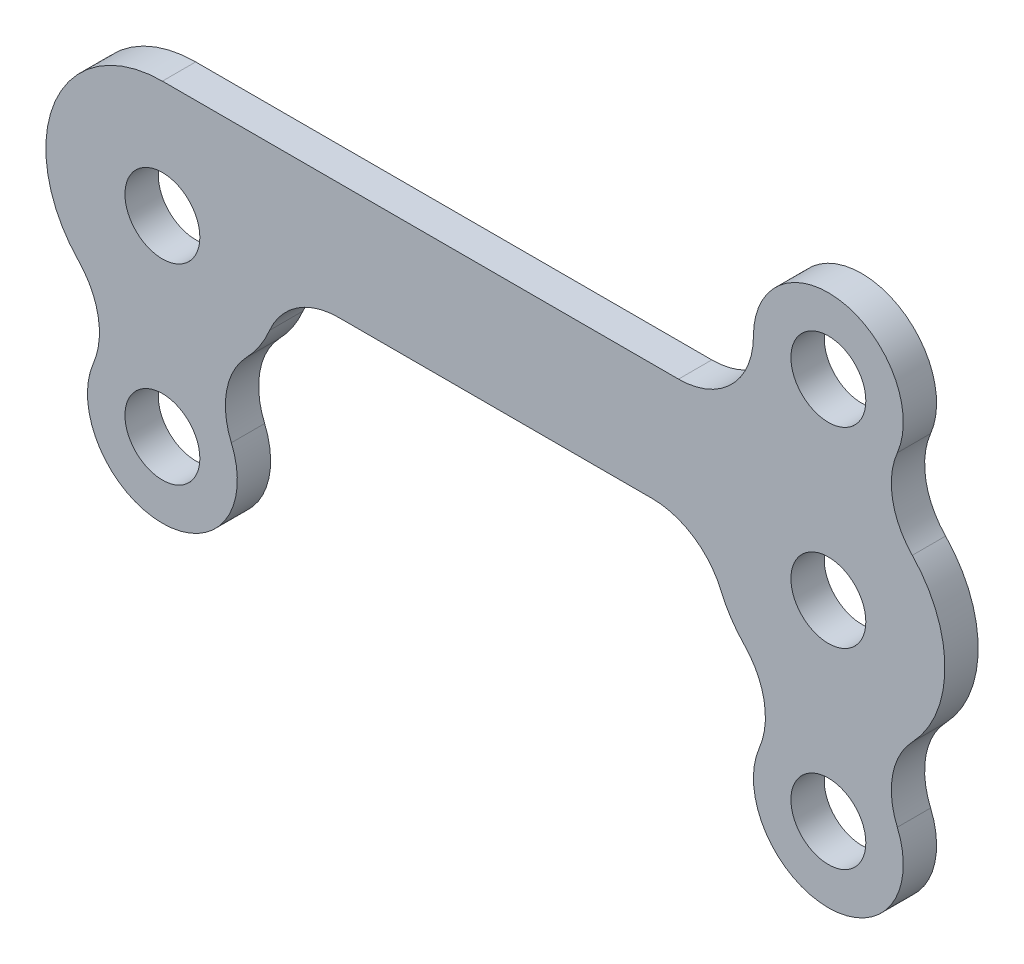
SolidWorks part; units mm, degrees
ref_plane "Front Plane" through (0, 0, 0) normal (0, 0, 1) x (1, 0, 0)
ref_plane "Top Plane" through (0, 0, 0) normal (0, 1, 0) x (1, 0, 0)
ref_plane "Right Plane" through (0, 0, 0) normal (1, 0, 0) x (0, 0, -1)
sketch "Sketch1" plane through (0, 0, 0) normal (0, 0, 1) x (1, 0, 0)
  line L11 (5.5562, 0) -> (26.1938, 0)
  line L12 (0, 5.5563) -> (31.75, 5.5563)
  circle A27 centre (0, 0) radius 5.5563 construction
  circle A28 centre (31.75, 0) radius 5.5562 construction
  arc A29 (0, 5.5563) -> (0, -5.5562) centre (0, 0) ccw
  arc A30 (31.75, -5.5562) -> (31.75, 5.5563) centre (31.75, 0) ccw
  circle A31 centre (0, 0) radius 1.7859
  circle A32 centre (31.75, 0) radius 1.7859
  arc A33 (0, -5.5562) -> (5.5562, 0) centre (0, 0) ccw
  arc A34 (26.1938, 0) -> (31.75, -5.5562) centre (31.75, 0) ccw
  circle A35 centre (0, -9.1281) radius 3.5719
  circle A36 centre (31.75, -9.1281) radius 1.7859
  circle A37 centre (0, -9.1281) radius 1.7859
  circle A38 centre (31.75, -9.1281) radius 3.5719
  circle A39 centre (-6.5741, -6.3327) radius 3.5719
  circle A40 centre (6.5741, -6.3327) radius 3.5719
  circle A41 centre (25.1759, -6.3327) radius 3.5719
  circle A42 centre (38.3241, -6.3327) radius 3.5719
  circle A43 centre (31.75, 9.1281) radius 1.7859
  circle A44 centre (31.75, 9.1281) radius 3.5719
  circle A45 centre (24.6062, 9.1281) radius 3.5719
  circle A46 centre (38.3241, 6.3327) radius 3.5719
  point P0 (0, 0)
  dimension "D8" = 31.75
  dimension "D9" = 11.1125
  dimension "D10" = 3.5719
  dimension "D11" = 7.1437
  dimension "D12" = 3.5719
extrude "Boss-Extrude1" add sketch "Sketch1" along normal blind 1.5875 contours L11 A34 A30 L12 A29 A33 A31 A32 | A35 A37 | A38 A36 | A44 A43 | A39 A35 A29 | A40 A33 A35 | A41 A38 A34 | A42 A30 A38 | A46 A44 A30 | A45 L12 A44
fillet "Fillet1" radius 3.5719 2 edges at (5.5562, 0, 0.7937) (26.1938, 0, 0.7937)
